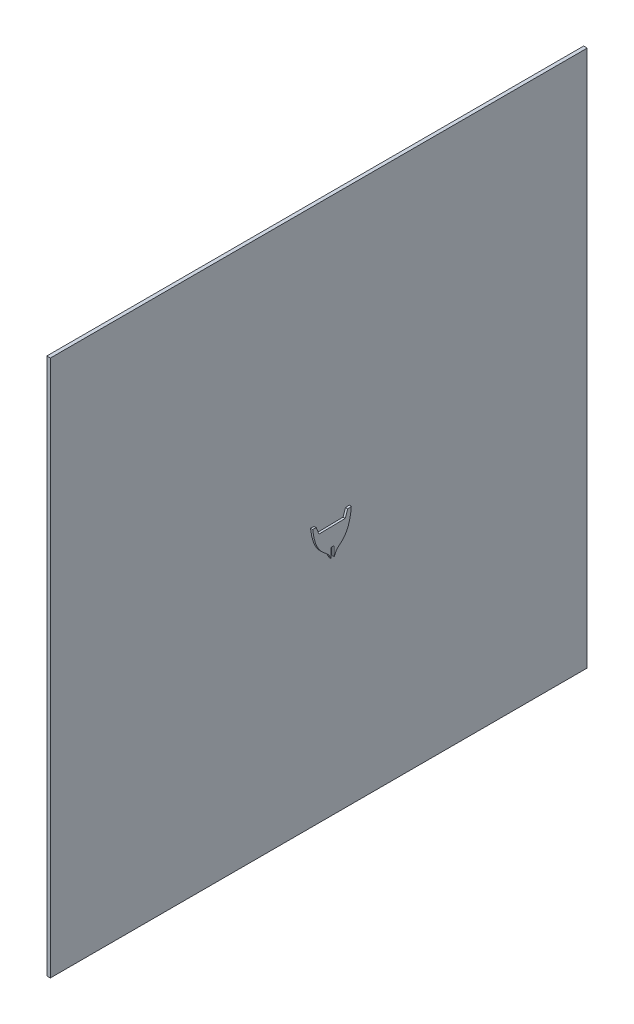
SolidWorks part; units mm, degrees
ref_plane "Plan de face" through (0, 0, 0) normal (0, 0, 1) x (1, 0, 0)
ref_plane "Plan de dessus" through (0, 0, 0) normal (0, 1, 0) x (1, 0, 0)
ref_plane "Plan de droite" through (0, 0, 0) normal (1, 0, 0) x (0, 0, -1)
sketch "Esquisse1" plane through (0, 0, 0) normal (0, 0, 1) x (1, 0, 0)
  point P0 (-20, 0)
  dimension "D1" = 20
sketch3d "Esquisse3D1"
  line L1 (-20, 1121.2893, 777.275) -> (-20, 1121.2893, -722.725)
  line L2 (-20, 1121.2893, 777.275) -> (-20, -378.7107, 777.275)
  line L3 (-20, -378.7107, 777.275) -> (-20, -378.7107, -722.725)
  line L4 (-20, 1121.2893, -722.725) -> (-20, -378.7107, -722.725)
  dimension "D1" = 1500
  dimension "D2" = 1500
extrude "Boss.-Extru.2" add sketch "Esquisse3D1" along direction (1, 0, 0) on the side of the normal blind 10 contours L2 L1 L4 L3
sketch "Esquisse4" plane through (-10, 0, 0) normal (1, 0, 0) x (0, 0, -1)
  line L0 (0, 0) -> (-7.701, 425.1082) construction
  line L1 (169.3944, 339.9131) -> (-188.5193, 333.4294) construction
  line L2 (-187.2006, 249.23) -> (169.0622, 255.6839) construction
  line L3 (-144.268, 175.2448) -> (126.4811, 180.1495) construction
sketch "Esquisse5" plane through (0, 0, 0) normal (1, 0, 0) x (0, 0, -1)
  line L0 (-7.701, 425.1082) -> (-4.4409, 245.146) construction
  line L1 (-42.7437, 336.0702) -> (30.5435, 337.3978)
  line L2 (-4.4409, 245.146) -> (5.2706, 286.9967) construction
  line L3 (5.2706, 286.9967) -> (14.3836, 279.4962) construction
  line L4 (14.3836, 279.4962) -> (42.3551, 288.3407) construction
  line L5 (42.3551, 288.3407) -> (47.5418, 358.0625) construction
  line L7 (0, 0) -> (-7.701, 425.1082) construction
  line L8 (47.5418, 358.0625) -> (37.3977, 357.038)
  line L9 (37.3977, 357.038) -> (30.5435, 337.3978)
  line L10 (169.3944, 339.9131) -> (-188.5193, 333.4294) construction
  line L16 (-144.268, 175.2448) -> (126.4811, 180.1495) construction
  line L18 (-4.4409, 245.146) -> (-15.6618, 286.6175) construction
  line L19 (-15.6618, 286.6175) -> (-24.4972, 278.7918) construction
  line L20 (-24.4972, 278.7918) -> (-52.7706, 286.6175) construction
  line L21 (-52.7706, 286.6175) -> (-60.4793, 356.1057) construction
  line L26 (-50.3047, 355.4493) -> (-42.7437, 336.0702)
  line L27 (-60.4793, 356.1057) -> (-50.3047, 355.4493)
  spline S0 degree 4 poles (-4.4409, 245.146) (5.2706, 286.9967) (14.3836, 279.4962) (42.3551, 288.3407) (47.5418, 358.0625) knots 0 0 0 0 0 1 1 1 1 1
  spline S1 degree 4 poles (-4.4409, 245.146) (-15.6618, 286.6175) (-24.4972, 278.7918) (-52.7706, 286.6175) (-60.4793, 356.1057) knots 0 0 0 0 0 1 1 1 1 1
  point P5 (-3.4084, 188.1495)
  point P14 (0, 0)
  point P15 (-29.2666, 230.628)
  point P17 (157.8531, 196.6453)
  point P18 (-137.6671, 314.5093)
  point P19 (63.2178, 206.539)
  point P20 (-107.3858, 310.2017)
  point P23 (-48.3582, 284.4825)
  point P24 (-48.3582, 244.4281)
  point P29 (-4.634, 255.8021)
  point P30 (-3.2209, 177.7999)
  point P31 (-29.385, 289.542)
  point P32 (-93.0505, 315.6828)
  point P35 (-58.2214, 335.7898)
  point P36 (-82.4133, 369.867)
  point P37 (-65.8171, 369.867)
  point P38 (-70.8803, 369.867)
  point P39 (-69.4739, 315.2963)
  point P40 (-41.9072, 291.9491)
  point P41 (-21.9355, 304.0446)
  point P42 (-5.0696, 279.8533)
  point P43 (-47.2801, 335.988)
  point P44 (-63.4332, 353.8082)
  point P45 (-61.1357, 315.4074)
  point P46 (-49.3201, 315.4074)
  point P47 (-31.5966, 300.3096)
  point P48 (-14.8578, 304.5764)
  point P49 (-50.3047, 355.4493)
  point P50 (-62.1203, 355.1211)
  point P51 (42.9075, 357.4185)
  point P52 (-60.4793, 356.1057)
  point P53 (-42.7437, 336.0702)
  point P54 (-3.7185, 205.2657)
  point P55 (-4.4409, 245.146)
  point P56 (-15.6618, 286.6175)
  point P57 (-24.4972, 278.7918)
  point P58 (-52.7706, 286.6175)
extrude "Boss.-Extru.3" add sketch "Esquisse5" along normal blind 6 separate body
sketch "Esquisse6" plane through (6, 0, 0) normal (1, 0, 0) x (0, 0, -1)
  line L0 (-9.2097, 259.9034) -> (-9.6988, 286.9034)
  line L1 (-9.6988, 286.9034) -> (-0.6988, 287.0665)
  line L2 (-0.6988, 287.0665) -> (-0.2097, 260.0665)
  line L3 (-0.2097, 260.0665) -> (117.0633, -47.527)
  line L4 (117.0633, -47.527) -> (-85.2277, -65.22)
  line L5 (-85.2277, -65.22) -> (-9.2097, 259.9034)
  line L6 (-9.2097, 259.9034) -> (-0.2097, 260.0665) construction
  line L7 (-144.268, 175.2448) -> (126.4811, 180.1495) construction
  spline S0 degree 4 poles (-60.4793, 356.1057) (-52.7706, 286.6175) (-24.4972, 278.7918) (-15.6618, 286.6175) (-4.4409, 245.146) knots 0 0 0 0 0 1 1 1 1 1 construction
  spline S1 degree 4 poles (-4.4409, 245.146) (5.2706, 286.9967) (14.3836, 279.4962) (42.3551, 288.3407) (47.5418, 358.0625) knots 0 0 0 0 0 1 1 1 1 1 construction
  dimension "D1" = 9
  dimension "D2" = 27
extrude "Enlèv. mat.-Extru.1" cut sketch "Esquisse6" against normal blind 6
